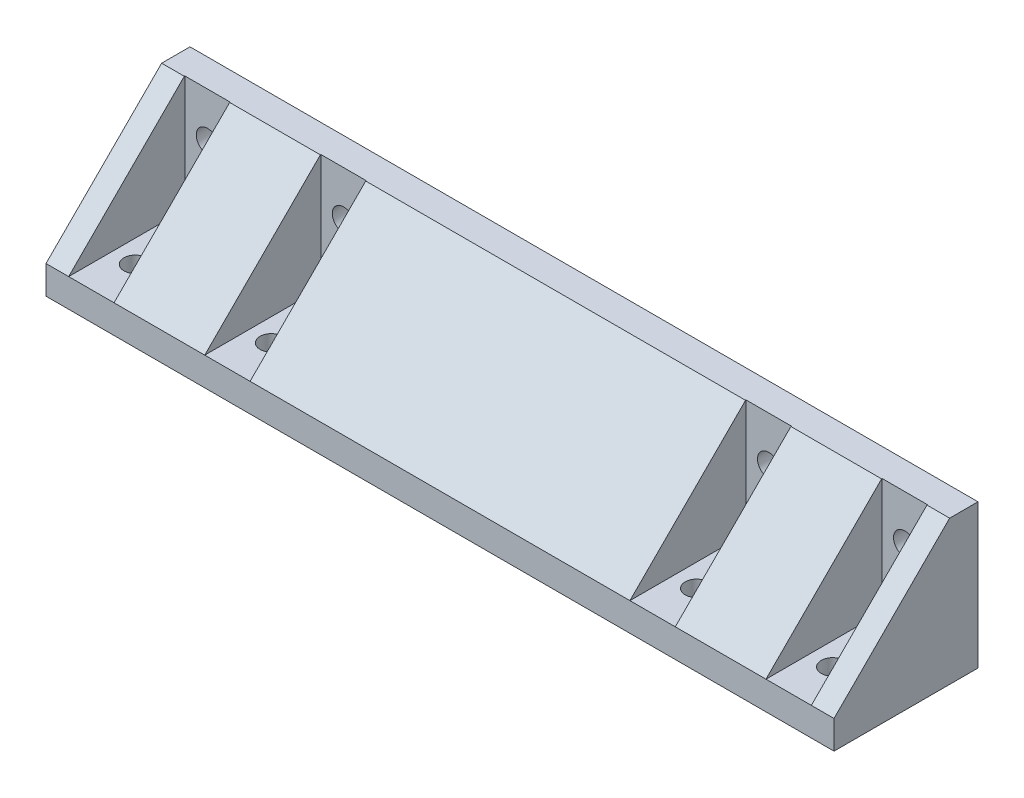
SolidWorks part; units mm, degrees
ref_plane "Front" through (0, 0, 0) normal (0, 0, 1) x (1, 0, 0)
ref_plane "Top" through (0, 0, 0) normal (0, 1, 0) x (1, 0, 0)
ref_plane "Right" through (0, 0, 0) normal (1, 0, 0) x (0, 0, -1)
sketch "Sketch1" plane through (0, 0, 0) normal (0, 1, 0) x (1, 0, 0)
  line L0 (0, 25.4) -> (0, 31.75)
  line L1 (0, 0) -> (139, 0)
  line L2 (0, 0) -> (0, 25.4)
  line L3 (0, 25.4) -> (139, 25.4)
  line L4 (139, 0) -> (139, 25.4)
  line L5 (0, 31.75) -> (0, 23.75)
  line L6 (0, 23.75) -> (0, 15.75)
  line L7 (0, 15.75) -> (0, 7.75)
  line L8 (0, 7.75) -> (0, -0.25)
  line L9 (0, 15.75) -> (139, 15.75)
  line L10 (0, 7.75) -> (139, 7.75)
  line L11 (0, 15.75) -> (8, 15.75)
  line L12 (8, 15.75) -> (16, 15.75)
  line L13 (16, 15.75) -> (24, 15.75)
  line L14 (24, 15.75) -> (32, 15.75)
  line L15 (32, 15.75) -> (107, 15.75)
  line L16 (107, 15.75) -> (131, 15.75)
  line L17 (0, 25.4) -> (0, 20.4)
  line L18 (0, 20.4) -> (139, 20.4)
  circle A0 centre (8, 15.75) radius 2
  circle A3 centre (32, 15.75) radius 2
  circle A5 centre (32, 7.75) radius 2
  circle A6 centre (8, 7.75) radius 2
  circle A7 centre (107, 15.75) radius 2
  circle A8 centre (131, 15.75) radius 2
  circle A9 centre (107, 7.75) radius 2
  circle A10 centre (131, 7.75) radius 2
  point P30 (0, 0)
  point P35 (139, 17.6804)
  dimension "D12" = 8
  dimension "D14" = 5
  dimension "D1" = 139
  dimension "D2" = 6.35
  dimension "D3" = 8
  dimension "D4" = 8
  dimension "D5" = 8
  dimension "D6" = 8
  dimension "D7" = 25.4
  dimension "D8" = 8
  dimension "D9" = 8
  dimension "D10" = 8
  dimension "D11" = 8
  dimension "D13" = 24
  dimension "D15" = 8
  dimension "D16" = 8
extrude "Boss-Extrude1" add sketch "Sketch1" along normal blind 5 contours A10 L10 L4 L9 A8 L16 A7 L15 A3 L12 A0 L2 A6 A5 A9 | A10 L10 A9 A5 A6 L2 L1 L4 | A8 L9 L4 L18 L2 A0 L12 A3 L15 A7 L16 | L6 L18 L4 L3 L2
sketch "Sketch3" plane through (0, 5, 0) normal (0, 1, 0) x (1, 0, 0)
  line L0 (0, 25.4) -> (139, 25.4)
  line L1 (0, 25.4) -> (0, 20.4)
  line L2 (139, 25.4) -> (139, 20.4)
  line L3 (0, 20.4) -> (139, 20.4)
  dimension "D1" = 5
extrude "Boss-Extrude2" add sketch "Sketch3" along normal blind 20.4
sketch "Sketch4" plane through (0, 5, 0) normal (0, 1, 0) x (1, 0, 0)
  line L1 (0, 20.4) -> (139, 20.4)
  line L2 (0, 20.4) -> (0, 0)
  line L3 (0, 0) -> (139, 0)
  line L4 (139, 20.4) -> (139, 0)
extrude "Boss-Extrude3" add sketch "Sketch4" along normal blind 20.5
sketch "Sketch5" plane through (139, 0, 0) normal (1, 0, 0) x (0, 0, -1)
  line L0 (20.4, 25.4) -> (0, 5)
  line L1 (0, 25.5) -> (0, 0) construction
  line M4 (20.4, 25.4) -> (20.4, 25.5)
  line M5 (20.4, 25.5) -> (0, 25.5)
  line M6 (0, 25.5) -> (0, 0)
  dimension "D1" = 5
extrude "Cut-Extrude1" cut sketch "Sketch5" against normal through all and the other way through all contours L0 M4 M5 M6
sketch "Sketch7" plane through (0, 0, 0) normal (0, 0, 1) x (1, 0, 0)
  line L0 (0, 0) -> (139, 0) construction
  line L1 (4, 0) -> (12, 0)
  line L2 (4, 0) -> (4, 25.4)
  line L3 (4, 25.4) -> (12, 25.4)
  line L4 (12, 0) -> (12, 25.4)
  line L5 (0, 5) -> (139, 5)
  line L6 (28, 0) -> (36, 0)
  line L7 (28, 0) -> (28, 25.4)
  line L8 (28, 25.4) -> (36, 25.4)
  line L9 (36, 0) -> (36, 25.4)
  line L10 (103, 0) -> (111, 0)
  line L11 (103, 0) -> (103, 25.4)
  line L12 (103, 25.4) -> (111, 25.4)
  line L13 (111, 0) -> (111, 25.4)
  line L14 (127, 0) -> (135, 0)
  line L15 (127, 0) -> (127, 25.4)
  line L16 (127, 25.4) -> (135, 25.4)
  line L17 (135, 0) -> (135, 25.4)
  line L18 (139, 5) -> (139, 0) construction
  line M10 (139, 5) -> (0, 5)
  dimension "D1" = 25.4
  dimension "D2" = 25.4
  dimension "D3" = 25.4
  dimension "D4" = 25.4
  dimension "D5" = 4
  dimension "D6" = 8
  dimension "D7" = 16
  dimension "D8" = 8
  dimension "D9" = 8
  dimension "D10" = 8
  dimension "D11" = 4
  dimension "D12" = 16
extrude "Cut-Extrude2" cut sketch "Sketch7" against normal blind 20.5 contours L4 L3 L2 M10 | L5 L9 L8 L7 | L5 L13 L12 L11 | L5 L17 L16 L15
sketch "Sketch8" plane through (0, 0, -20.5) normal (0, 0, 1) x (1, 0, 0)
  line L0 (131, 25.4) -> (131, 17.4)
  line L1 (127, 25.4) -> (135, 25.4) construction
  line L2 (107, 25.4) -> (107, 17.4)
  line L3 (103, 25.4) -> (111, 25.4) construction
  line L4 (32, 25.4) -> (32, 17.4)
  line L5 (28, 25.4) -> (36, 25.4) construction
  line L6 (8, 25.4) -> (8, 17.4)
  line L7 (4, 25.4) -> (12, 25.4) construction
  circle A0 centre (8, 17.4) radius 2
  circle A1 centre (32, 17.4) radius 2
  circle A2 centre (107, 17.4) radius 2
  circle A3 centre (131, 17.4) radius 2
  dimension "D1" = 8
extrude "Cut-Extrude3" cut sketch "Sketch8" against normal blind 10
